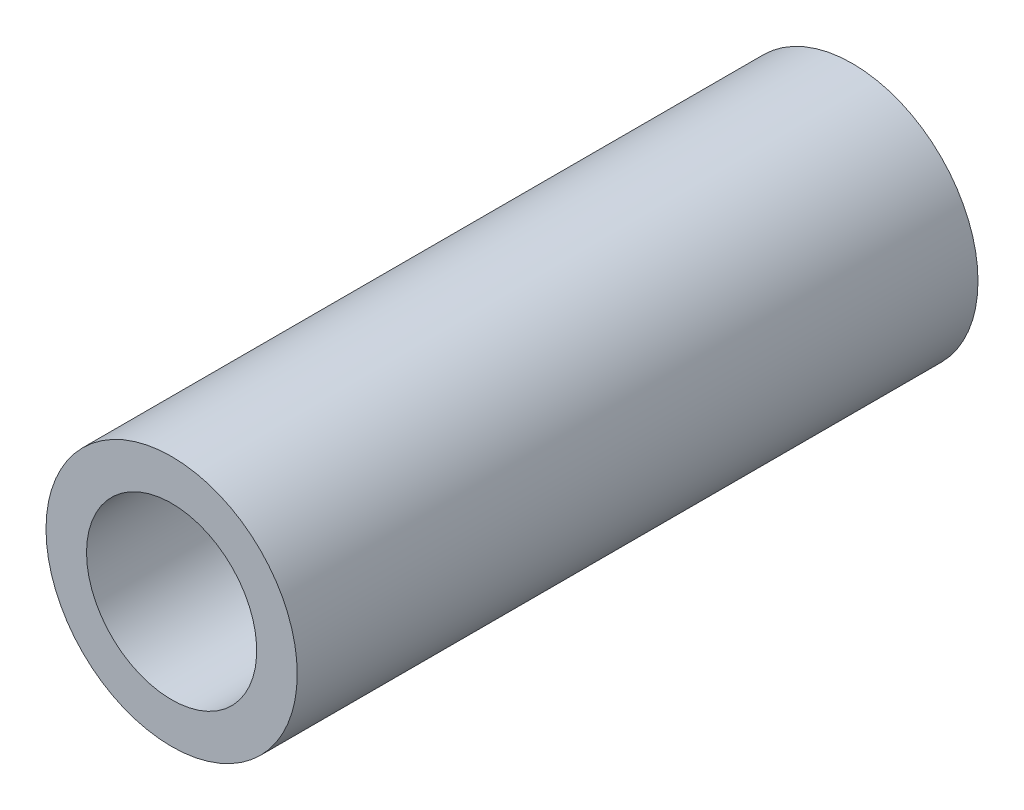
SolidWorks part; units mm, degrees
ref_plane "Спереди" through (0, 0, 0) normal (0, 0, 1) x (1, 0, 0)
ref_plane "Сверху" through (0, 0, 0) normal (0, 1, 0) x (1, 0, 0)
ref_plane "Справа" through (0, 0, 0) normal (1, 0, 0) x (0, 0, -1)
sketch "Эскиз1" plane through (0, 0, 0) normal (0, 0, 1) x (1, 0, 0)
  circle A0 centre (0, 0) radius 10.5
  circle A1 centre (0, 0) radius 15.5
  dimension "D1" = 21
  dimension "D2" = 31
extrude "Бобышка-Вытянуть1" add sketch "Эскиз1" along normal blind 84
